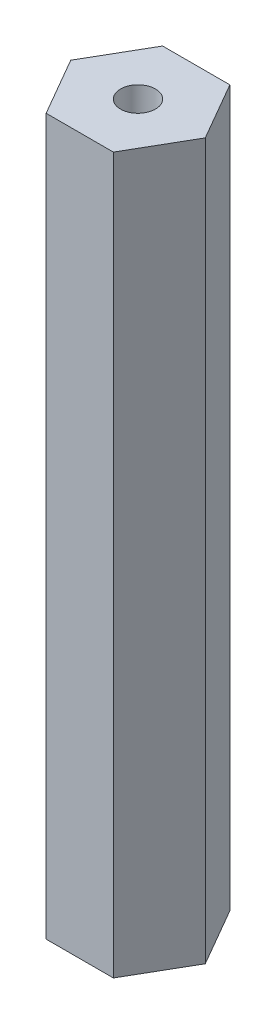
SolidWorks part; units mm, degrees
ref_plane "Спереди" through (0, 0, 0) normal (0, 0, 1) x (1, 0, 0)
ref_plane "Сверху" through (0, 0, 0) normal (0, 1, 0) x (1, 0, 0)
ref_plane "Справа" through (0, 0, 0) normal (1, 0, 0) x (0, 0, -1)
sketch "Эскиз1" plane through (0, 0, 0) normal (0, 1, 0) x (1, 0, 0)
  line L1 (2.8868, 0) -> (1.4434, 2.5)
  line L2 (1.4434, 2.5) -> (-1.4434, 2.5)
  line L3 (-1.4434, 2.5) -> (-2.8868, 0)
  line L4 (-2.8868, 0) -> (-1.4434, -2.5)
  line L5 (-1.4434, -2.5) -> (1.4434, -2.5)
  line L6 (1.4434, -2.5) -> (2.8868, 0)
  circle A0 centre (0, 0) radius 2.5 construction
  dimension "D1" = 5
extrude "Бобышка-Вытянуть1" add sketch "Эскиз1" along normal blind 30.7
sketch "Эскиз2" plane through (0, 30.7, 0) normal (0, 1, 0) x (1, 0, 0)
  circle A0 centre (0, 0) radius 0.75
  dimension "D1" = 1.5
extrude "Вырез-Вытянуть1" cut sketch "Эскиз2" against normal through all
